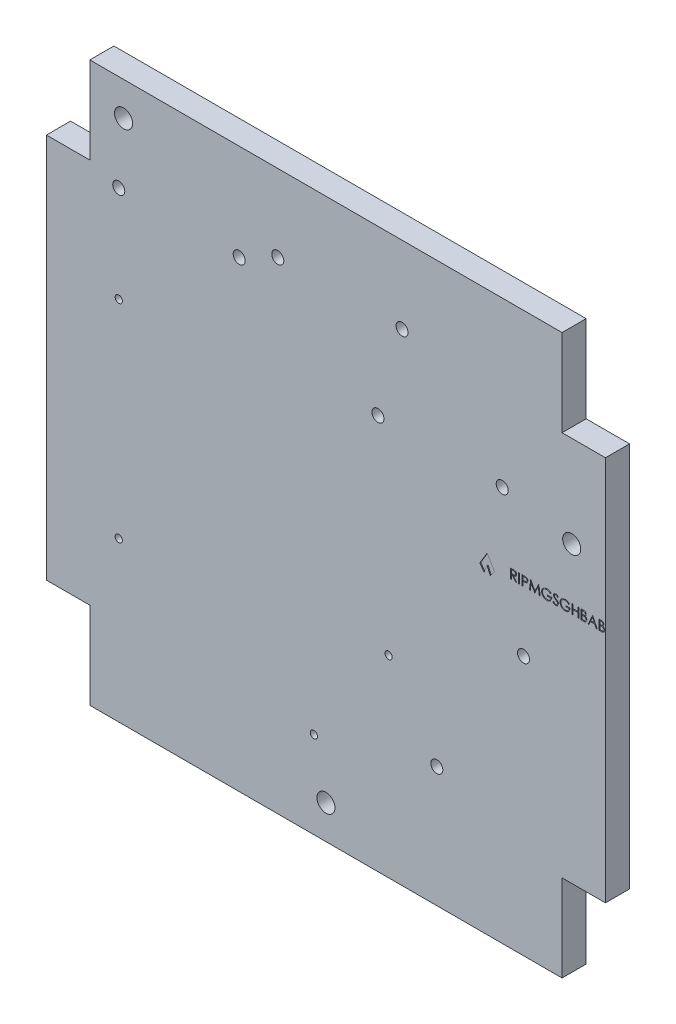
SolidWorks part; units mm, degrees
ref_plane "Płaszczyzna przednia" through (0, 0, 0) normal (0, 0, 1) x (1, 0, 0)
ref_plane "Płaszczyzna górna" through (0, 0, 0) normal (0, 1, 0) x (1, 0, 0)
ref_plane "Płaszczyzna prawa" through (0, 0, 0) normal (1, 0, 0) x (0, 0, -1)
sketch "Szkic2" plane through (0, 0, 0) normal (0, 0, 1) x (1, 0, 0)
  line L1 (0, 0) -> (116, 0)
  line L2 (0, 0) -> (0, 116)
  line L3 (0, 116) -> (116, 116)
  line L4 (116, 0) -> (116, 116)
  line L5 (0, 98) -> (9, 98)
  line L6 (0, 98) -> (0, 116)
  line L7 (0, 116) -> (9, 116)
  line L8 (9, 98) -> (9, 116)
  line L9 (107, 98) -> (116, 98)
  line L10 (107, 98) -> (107, 116)
  line L11 (107, 116) -> (116, 116)
  line L12 (116, 98) -> (116, 116)
  line L13 (107, 18) -> (116, 18)
  line L14 (107, 18) -> (107, 0)
  line L15 (107, 0) -> (116, 0)
  line L16 (116, 18) -> (116, 0)
  line L17 (0, 18) -> (9, 18)
  line L18 (0, 18) -> (0, 0)
  line L19 (0, 0) -> (9, 0)
  line L20 (9, 18) -> (9, 0)
  circle A0 centre (15, 96) radius 1.25
  circle A1 centre (40, 96) radius 1.25
  circle A2 centre (48, 100) radius 1.25
  circle A3 centre (68.7906, 82) radius 1.25
  circle A4 centre (73.7906, 100) radius 1.25
  circle A5 centre (94.5812, 82) radius 1.25
  circle A6 centre (15, 76) radius 0.75
  circle A7 centre (71, 40) radius 0.75
  circle A8 centre (15, 33) radius 0.75
  circle A9 centre (55.5, 18) radius 0.75
  circle A10 centre (81, 25) radius 1.25
  circle A11 centre (99, 53.8444) radius 1.25
  circle A12 centre (16, 109) radius 1.875
  circle A13 centre (58, 7) radius 1.875
  circle A14 centre (109, 79) radius 1.875
  dimension "D11" = 2.5
  dimension "D12" = 20
  dimension "D13" = 15
  dimension "D14" = 2.5
  dimension "D15" = 20
  dimension "D16" = 25
  dimension "D17" = 2.5
  dimension "D18" = 16
  dimension "D19" = 8
  dimension "D20" = 2.5
  dimension "D21" = 18
  dimension "D22" = 27.5
  dimension "D23" = 2.5
  dimension "D24" = 5
  dimension "D25" = 18
  dimension "D26" = 2.5
  dimension "D27" = 27.5
  dimension "D28" = 18
  dimension "D29" = 1.5
  dimension "D30" = 1.5
  dimension "D31" = 15
  dimension "D32" = 56
  dimension "D33" = 36
  dimension "D34" = 20
  dimension "D35" = 1.5
  dimension "D36" = 1.5
  dimension "D37" = 33
  dimension "D38" = 40.5
  dimension "D39" = 15
  dimension "D40" = 15
  dimension "D41" = 2.5
  dimension "D42" = 25
  dimension "D43" = 35
  dimension "D44" = 2.5
  dimension "D45" = 18
  dimension "D46" = 34
  dimension "D47" = 3.75
  dimension "D48" = 7
  dimension "D49" = 7
  dimension "D50" = 3.75
  dimension "D51" = 58
  dimension "D52" = 7
  dimension "D53" = 3.75
  dimension "D54" = 7
  dimension "D1" = 116
  dimension "D2" = 116
  dimension "D3" = 18
  dimension "D4" = 9
  dimension "D5" = 18
  dimension "D6" = 9
  dimension "D7" = 18
  dimension "D8" = 9
  dimension "D9" = 18
  dimension "D10" = 9
  dimension "D55" = 37
extrude "Dodanie-wyciągnięcie1" add sketch "Szkic2" along normal blind 5 contours L17 L20 L1 L14 L13 L4 L9 L10 L3 L8 L5 L2 A11 A10 A9 A8 A7 A6 A5 A4 A3 A2 A1 A0
sketch "Szkic4" plane through (0, 0, 5) normal (0, 0, 1) x (1, 0, 0)
  line L0 (116, 66.3444) -> (-2.5854, 66.3444) construction
  line L1 (116, 18) -> (116, 98) construction
  line L2 (91.4526, 66.3444) -> (91.4526, 70.8181) construction
  line L3 (91.4526, 66.3444) -> (91.4526, 63.42) construction
  line L4 (91.4526, 66.3444) -> (90.8159, 64.8444)
  line L5 (90.8159, 64.8444) -> (89.9132, 66.0423)
  line L6 (89.9132, 66.0423) -> (91.4526, 68.5812)
  line L7 (91.4526, 66.3444) -> (92.0894, 64.8444)
  line L8 (92.0894, 64.8444) -> (92.9921, 66.0423)
  line L9 (92.9921, 66.0423) -> (91.4526, 68.5812)
  text T0 "RIPMGSGHBAB" font "Century Gothic" height 2
  dimension "D1" = 1.5
  dimension "D2" = 1.5
  dimension "D3" = 60
  dimension "D4" = 23
extrude "Wytnij-wyciągnięcie1" cut sketch "Szkic4" against normal blind 0.2
